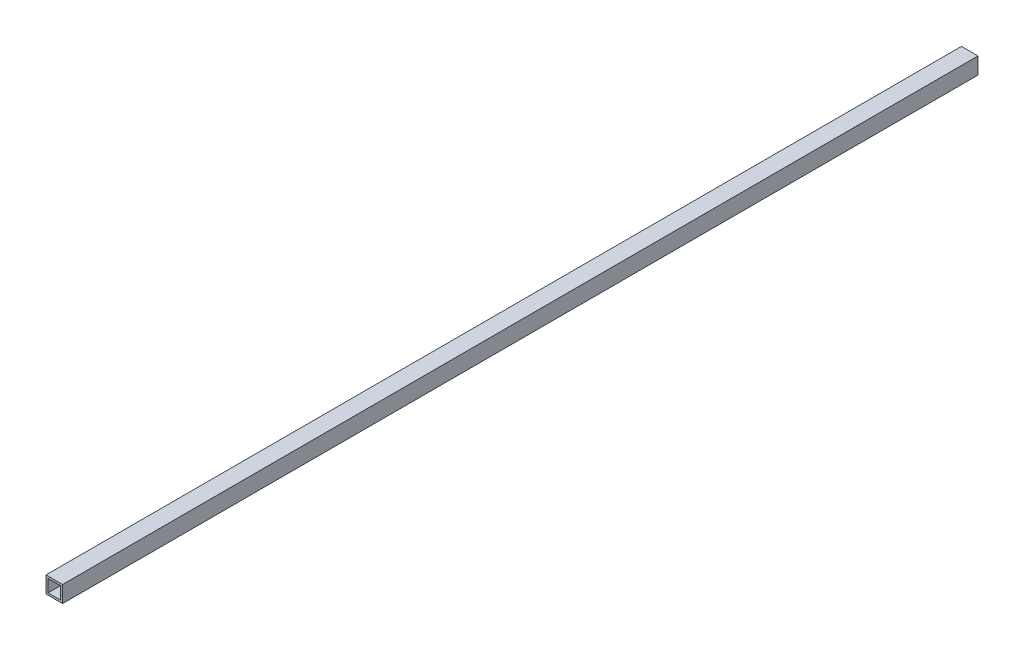
SolidWorks part; units mm, degrees
ref_plane "Front Plane" through (0, 0, 0) normal (0, 0, 1) x (1, 0, 0)
ref_plane "Top Plane" through (0, 0, 0) normal (0, 1, 0) x (1, 0, 0)
ref_plane "Right Plane" through (0, 0, 0) normal (1, 0, 0) x (0, 0, -1)
sketch "Sketch1" plane through (0, 0, 0) normal (0, 0, 1) x (1, 0, 0)
  line L0 (-4.7625, 4.7625) -> (4.7625, 4.7625)
  line L1 (-6.35, -6.35) -> (6.35, -6.35)
  line L2 (-6.35, -6.35) -> (-6.35, 6.35)
  line L3 (-6.35, 6.35) -> (6.35, 6.35)
  line L4 (6.35, -6.35) -> (6.35, 6.35)
  line L5 (-6.35, -6.35) -> (6.35, 6.35) construction
  line L6 (-6.35, 6.35) -> (6.35, -6.35) construction
  line L7 (4.7625, -4.7625) -> (4.7625, 4.7625)
  line L8 (-4.7625, -4.7625) -> (4.7625, -4.7625)
  line L9 (-4.7625, -4.7625) -> (-4.7625, 4.7625)
  point P0 (0, 0)
  dimension "D1" = 12.7
  dimension "D2" = 12.7
  dimension "D3" = 1.5875
extrude "Boss-Extrude1" add sketch "Sketch1" along normal mid plane 701.675
